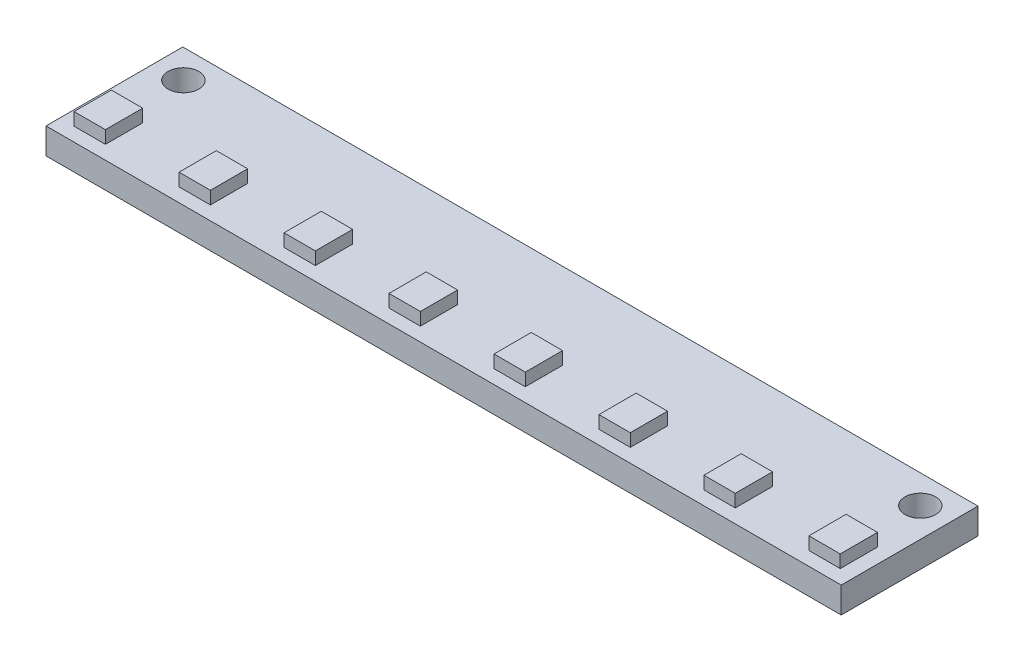
SolidWorks part; units mm, degrees
ref_plane "Front Plane" through (0, 0, 0) normal (0, 0, 1) x (1, 0, 0)
ref_plane "Top Plane" through (0, 0, 0) normal (0, 1, 0) x (1, 0, 0)
ref_plane "Right Plane" through (0, 0, 0) normal (1, 0, 0) x (0, 0, -1)
sketch "Sketch4" plane through (0, 0, 0) normal (0, 1, 0) x (1, 0, 0)
  line L1 (-37.5, -6.45) -> (37.5, -6.45)
  line L2 (-37.5, -6.45) -> (-37.5, 6.45)
  line L3 (-37.5, 6.45) -> (37.5, 6.45)
  line L4 (37.5, -6.45) -> (37.5, 6.45)
  line L5 (-37.5, -6.45) -> (37.5, 6.45) construction
  line L6 (-37.5, 6.45) -> (37.5, -6.45) construction
  point P0 (0, 0)
  dimension "D1" = 75
  dimension "D2" = 12.9
extrude "Boss-Extrude3" add sketch "Sketch4" along normal blind 2.45
sketch "Sketch5" plane through (0, 2.45, 0) normal (0, 1, 0) x (1, 0, 0)
  line L0 (0, 6.45) -> (0, 3.76) construction
  line L1 (37.5, 6.45) -> (-37.5, 6.45) construction
  line L2 (0, 3.76) -> (-33.3, 3.76) construction
  line L3 (0, 3.76) -> (33.3, 3.76) construction
  line L4 (33.3, 3.76) -> (34.75, 3.76) construction
  line L5 (-33.3, 3.76) -> (-34.75, 3.76) construction
  circle A0 centre (34.75, 3.76) radius 1.45
  circle A1 centre (-34.75, 3.76) radius 1.45
  dimension "D6" = 2.9
  dimension "D7" = 2.9
  dimension "D1" = 33.3
  dimension "D2" = 33.3
  dimension "D3" = 2.69
  dimension "D4" = 1.45
  dimension "D5" = 1.45
extrude "Cut-Extrude2" cut sketch "Sketch5" against normal blind 2.45
sketch "Sketch6" plane through (0, 2.45, 0) normal (0, 1, 0) x (1, 0, 0)
  line L0 (26.2078, -5.1526) -> (26.2078, -1.6376)
  line L1 (36.1078, -5.1526) -> (33.1521, -5.1526)
  line L2 (36.1078, -5.1526) -> (36.1078, -1.6376)
  line L3 (36.1078, -1.6376) -> (33.1521, -1.6376)
  line L4 (33.1521, -5.1526) -> (33.1521, -1.6376)
  line L5 (26.2078, -5.1526) -> (23.2521, -5.1526)
  line L6 (23.2521, -5.1526) -> (23.2521, -1.6376)
  line L7 (26.2078, -1.6376) -> (23.2521, -1.6376)
  line L8 (16.3078, -5.1526) -> (16.3078, -1.6376)
  line L9 (16.3078, -5.1526) -> (13.3521, -5.1526)
  line L10 (13.3521, -5.1526) -> (13.3521, -1.6376)
  line L11 (16.3078, -1.6376) -> (13.3521, -1.6376)
  line L12 (6.4078, -5.1526) -> (6.4078, -1.6376)
  line L13 (6.4078, -5.1526) -> (3.4521, -5.1526)
  line L14 (3.4521, -5.1526) -> (3.4521, -1.6376)
  line L15 (6.4078, -1.6376) -> (3.4521, -1.6376)
  line L16 (-3.4922, -5.1526) -> (-3.4922, -1.6376)
  line L17 (-3.4922, -5.1526) -> (-6.4479, -5.1526)
  line L18 (-6.4479, -5.1526) -> (-6.4479, -1.6376)
  line L19 (-3.4922, -1.6376) -> (-6.4479, -1.6376)
  line L20 (-13.3922, -5.1526) -> (-13.3922, -1.6376)
  line L21 (-13.3922, -5.1526) -> (-16.3479, -5.1526)
  line L22 (-16.3479, -5.1526) -> (-16.3479, -1.6376)
  line L23 (-13.3922, -1.6376) -> (-16.3479, -1.6376)
  line L24 (-23.2922, -5.1526) -> (-23.2922, -1.6376)
  line L25 (-23.2922, -5.1526) -> (-26.2479, -5.1526)
  line L26 (-26.2479, -5.1526) -> (-26.2479, -1.6376)
  line L27 (-23.2922, -1.6376) -> (-26.2479, -1.6376)
  line L28 (-33.1922, -5.1526) -> (-33.1922, -1.6376)
  line L29 (-33.1922, -5.1526) -> (-36.1479, -5.1526)
  line L30 (-36.1479, -5.1526) -> (-36.1479, -1.6376)
  line L31 (-33.1922, -1.6376) -> (-36.1479, -1.6376)
  dimension "D1" = 8
extrude "Boss-Extrude4" add sketch "Sketch6" along normal blind 1.2
